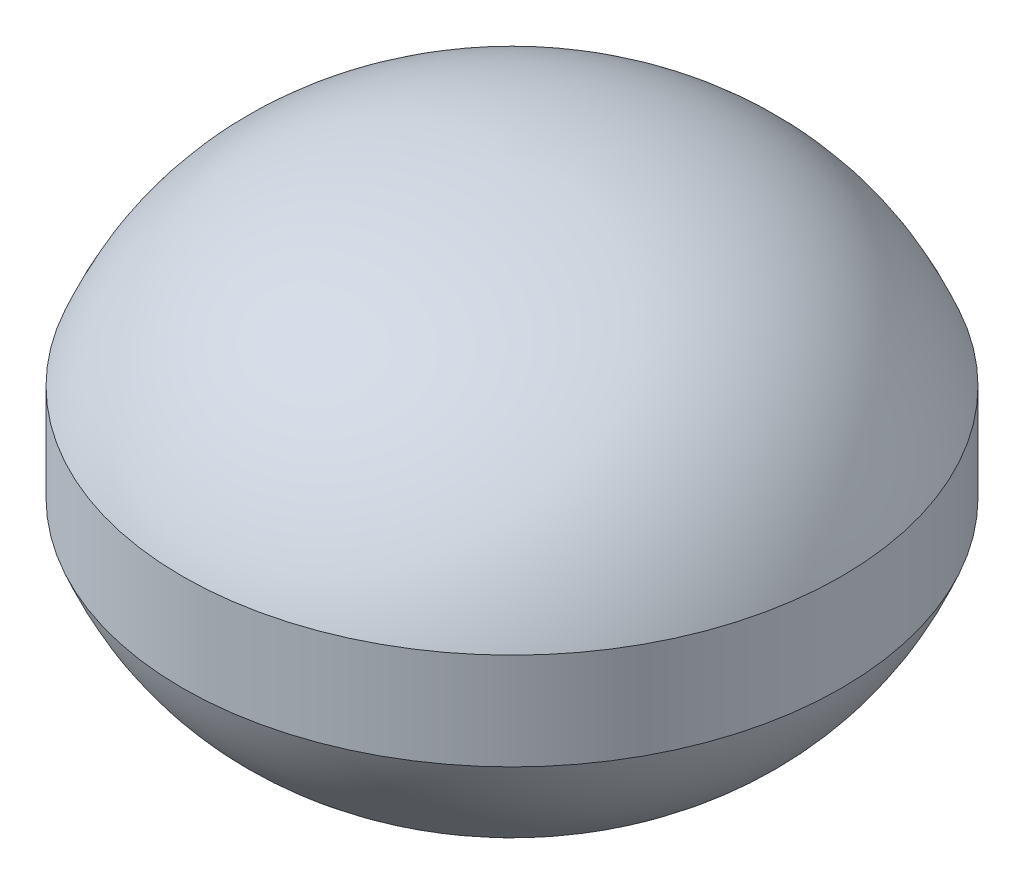
SolidWorks part; units mm, degrees
ref_plane "Front Plane" through (0, 0, 0) normal (0, 0, 1) x (1, 0, 0)
ref_plane "Top Plane" through (0, 0, 0) normal (0, 1, 0) x (1, 0, 0)
ref_plane "Right Plane" through (0, 0, 0) normal (1, 0, 0) x (0, 0, -1)
sketch "Sketch4" plane through (0, 0, 0) normal (0, 1, 0) x (1, 0, 0)
  circle A0 centre (0, 0) radius 450.85
  dimension "D1" = 901.7
extrude "Boss-Extrude2" add sketch "Sketch4" along normal mid plane 132.4
sketch "Sketch7" plane through (0, 0, 0) normal (1, 0, 0) x (0, 0, -1)
  line L0 (0, -336.55) -> (0, 336.55) construction
sketch "Sketch10" plane through (0, 0, 0) normal (0, 0, 1) x (1, 0, 0)
  line L0 (0, -336.55) -> (0, 336.55) construction
  line L1 (-450.85, 66.2) -> (0, 66.2)
  line L2 (450.85, 66.2) -> (-450.85, 66.2) construction
  line L3 (0, 66.2) -> (0, 336.55)
  line L4 (0, 0) -> (0, 163.5958) construction
  line L5 (0, 0) -> (-297.6149, 0) construction
  line L6 (-450.85, -66.2) -> (0, -66.2)
  line L7 (0, -66.2) -> (0, -336.55)
  spline S0 degree 2 poles (-450.85, 66.2) (-347.7113, 328.6593) (0, 336.55) knots 0 0 0 1 1 1
  spline S1 degree 2 poles (-450.85, -66.2) (-347.7113, -328.6593) (0, -336.55) knots 0 0 0 1 1 1
revolve "Revolve7" add sketch "Sketch10" angle 360 about L4
ref_plane "Plane1" through (0, 10, 0) normal (0, 1, 0) x (1, 0, 0)
